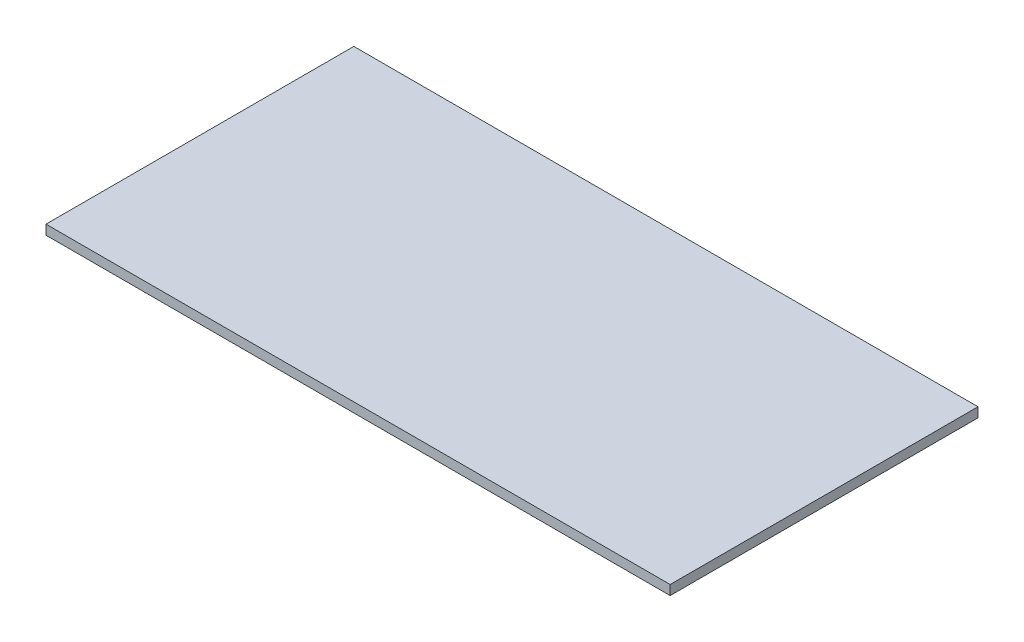
SolidWorks part; units mm, degrees
ref_plane "Front Plane" through (0, 0, 0) normal (0, 0, 1) x (1, 0, 0)
ref_plane "Top Plane" through (0, 0, 0) normal (0, 1, 0) x (1, 0, 0)
ref_plane "Right Plane" through (0, 0, 0) normal (1, 0, 0) x (0, 0, -1)
sketch "Sketch1" plane through (0, 0, 0) normal (0, 1, 0) x (1, 0, 0)
  line L1 (-59.1289, 123.9995) -> (249.8711, 123.9995)
  line L2 (-59.1289, 123.9995) -> (-59.1289, -28.4005)
  line L3 (-59.1289, -28.4005) -> (249.8711, -28.4005)
  line L4 (249.8711, 123.9995) -> (249.8711, -28.4005)
  dimension "D1" = 309
  dimension "D2" = 152.4
extrude "Boss-Extrude2" add sketch "Sketch1" along normal blind 4.7625
